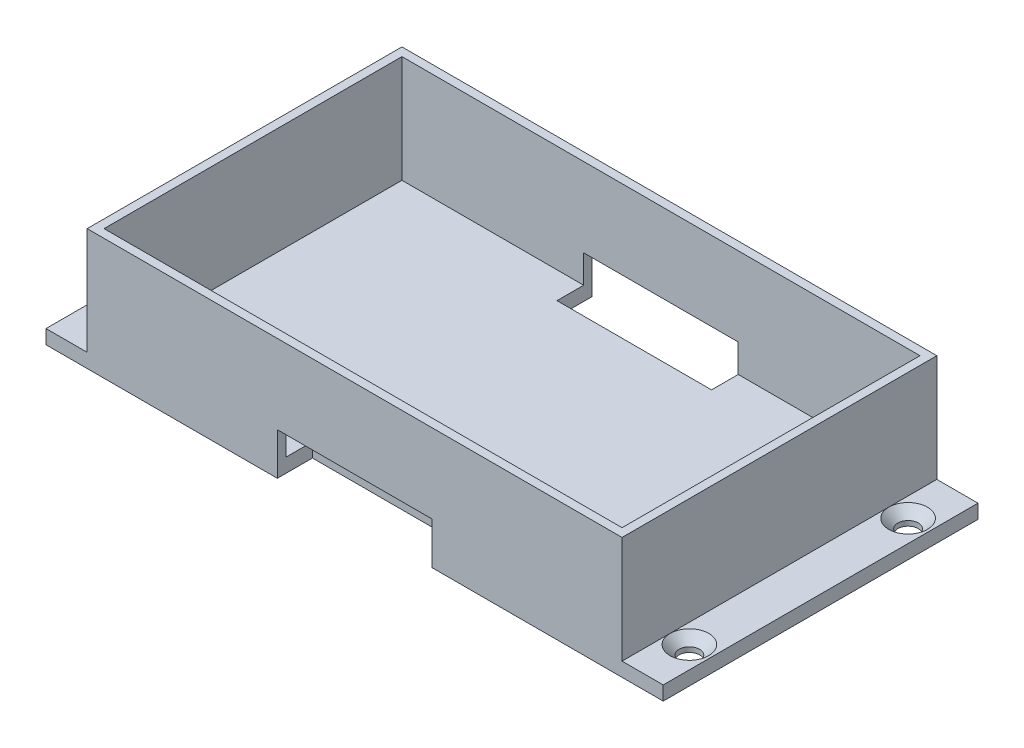
SolidWorks part; units mm, degrees
ref_plane "Front Plane" through (0, 0, 0) normal (0, 0, 1) x (1, 0, 0)
ref_plane "Top Plane" through (0, 0, 0) normal (0, 1, 0) x (1, 0, 0)
ref_plane "Right Plane" through (0, 0, 0) normal (1, 0, 0) x (0, 0, -1)
sketch "Sketch1" plane through (0, 0, 0) normal (0, 1, 0) x (1, 0, 0)
  line L1 (-43.93, 22.405) -> (43.93, 22.405)
  line L2 (-43.93, 22.405) -> (-43.93, -22.405)
  line L3 (-43.93, -22.405) -> (43.93, -22.405)
  line L4 (43.93, 22.405) -> (43.93, -22.405)
  line L5 (-43.93, 22.405) -> (43.93, -22.405) construction
  line L6 (-43.93, -22.405) -> (43.93, 22.405) construction
  point P0 (0, 0)
  dimension "D1" = 87.86
  dimension "D2" = 44.81
extrude "Boss-Extrude1" add sketch "Sketch1" along normal blind 2
hole_wizard "CSK for M2.5 Countersunk Flat Head Screw1" positions "Sketch2" profile "Sketch3" countersink size "M2.5" standard "ISO" end condition through all
sketch "Sketch2" plane through (0, 2, 0) normal (0, 1, 0) x (1, 0, 0)
  line L0 (-43.93, 22.405) -> (-43.93, -22.405) construction
  line L1 (43.93, -22.405) -> (43.93, 22.405) construction
  line L2 (43.93, 22.405) -> (-43.93, 22.405) construction
  line L3 (-43.93, -22.405) -> (43.93, -22.405) construction
  point P0 (-40.82, 15.565)
  point P2 (-40.82, -15.565)
  point P4 (40.82, -15.565)
  point P6 (40.82, 15.565)
  dimension "D1" = 3.11
  dimension "D2" = 3.11
  dimension "D3" = 3.11
  dimension "D4" = 3.11
  dimension "D5" = 6.84
  dimension "D6" = 6.84
  dimension "D7" = 6.84
  dimension "D8" = 6.84
sketch "Sketch3" plane through (-40.82, 2, -15.565) normal (1, 0, 0) x (0, 0, 1)
  line L0 (0, 0) -> (0, 2)
  line L1 (0, 2) -> (1.45, 2)
  line L2 (1.45, 2) -> (1.45, 1.3)
  line L3 (1.45, 1.3) -> (2.75, 0)
  line L5 (2.75, 0) -> (0, 0)
  line L6 (-1.45, 1.3) -> (-2.75, 0) construction
  line L11 (0, -6.35) -> (0, 107.95) construction
  dimension "Thru Hole Dia." = 2.9
  dimension "Thru Hole Depth" = 2
  dimension "Near C'Sink Dia." = 5.5
  dimension "Near C'Sink Angle" = 90
sketch "Sketch5" plane through (0, 2, 0) normal (0, 1, 0) x (1, 0, 0)
  line L0 (-38.07, 15.565) -> (-38.07, 22.405)
  line L1 (43.93, 22.405) -> (-43.93, 22.405) construction
  line L2 (-38.07, 22.405) -> (-36.87, 22.405)
  line L3 (-36.87, 22.405) -> (-36.87, -22.405)
  line L4 (-43.93, -22.405) -> (43.93, -22.405) construction
  line L5 (-36.87, -22.405) -> (-38.07, -22.405)
  line L6 (-38.07, -22.405) -> (-38.07, 15.565)
  circle A0 centre (-40.82, 15.565) radius 2.75 construction
  dimension "D1" = 1.2
extrude "Boss-Extrude2" add sketch "Sketch5" along normal blind 15.25
sketch "Sketch6" plane through (0, 2, 0) normal (0, 1, 0) x (1, 0, 0)
  line L0 (-36.87, 22.405) -> (38.07, 22.405)
  line L1 (43.93, 22.405) -> (-36.87, 22.405) construction
  line L2 (38.07, 22.405) -> (38.07, -22.405)
  line L3 (-36.87, -22.405) -> (43.93, -22.405) construction
  line L4 (38.07, -22.405) -> (-36.87, -22.405)
  line L5 (-36.87, -22.405) -> (-36.87, -21.205)
  line L6 (-36.87, -22.405) -> (-36.87, 22.405) construction
  line L7 (-36.87, -21.205) -> (36.87, -21.205)
  line L8 (36.87, -21.205) -> (36.87, 21.205)
  line L9 (36.87, 21.205) -> (-36.87, 21.205)
  line L10 (-36.87, 21.205) -> (-36.87, 22.405)
  line L11 (-36.87, -22.405) -> (-36.87, 22.405) construction
  circle A0 centre (40.82, -15.565) radius 2.75 construction
  dimension "D4" = 77.69
  dimension "D5" = 74.94
  dimension "D1" = 1.2
  dimension "D2" = 1.2
  dimension "D3" = 1.2
extrude "Boss-Extrude3" add sketch "Sketch6" along normal blind 15.25
sketch "Sketch7" plane through (0, 0, -21.205) normal (0, 0, 1) x (1, 0, 0)
  line L0 (0, 2) -> (-11, 2)
  line L1 (-36.87, 2) -> (36.87, 2) construction
  line L2 (-11, 2) -> (-11, 6)
  line L3 (-11, 6) -> (11, 6)
  line L4 (11, 6) -> (11, 2)
  line L5 (11, 2) -> (0, 2)
  dimension "D1" = 11
  dimension "D2" = 11
  dimension "D3" = 4
extrude "Cut-Extrude1" cut sketch "Sketch7" against normal blind 15.25 and the other way blind 50
sketch "Sketch10" plane through (0, 2, 0) normal (0, 1, 0) x (1, 0, 0)
  line L0 (-11, 21.205) -> (-11, 22.405)
  line L1 (-11, 22.405) -> (11, 22.405)
  line L2 (38.07, 22.405) -> (-38.07, 22.405) construction
  line L3 (11, 22.405) -> (11, 17.405)
  line L4 (11, 17.405) -> (-11, 17.405)
  line L5 (-11, 17.405) -> (-11, 21.205)
  dimension "D1" = 5
extrude "Cut-Extrude4" cut sketch "Sketch10" against normal blind 15.25
sketch "Sketch11" plane through (0, 2, 0) normal (0, 1, 0) x (1, 0, 0)
  line L1 (-11, -22.405) -> (11, -22.405)
  line L2 (11, -22.405) -> (11, -17.405)
  line L3 (11, -17.405) -> (-11, -17.405)
  line L4 (-11, -17.405) -> (-11, -22.405)
  dimension "D1" = 5
extrude "Cut-Extrude5" cut sketch "Sketch11" against normal blind 15.25
